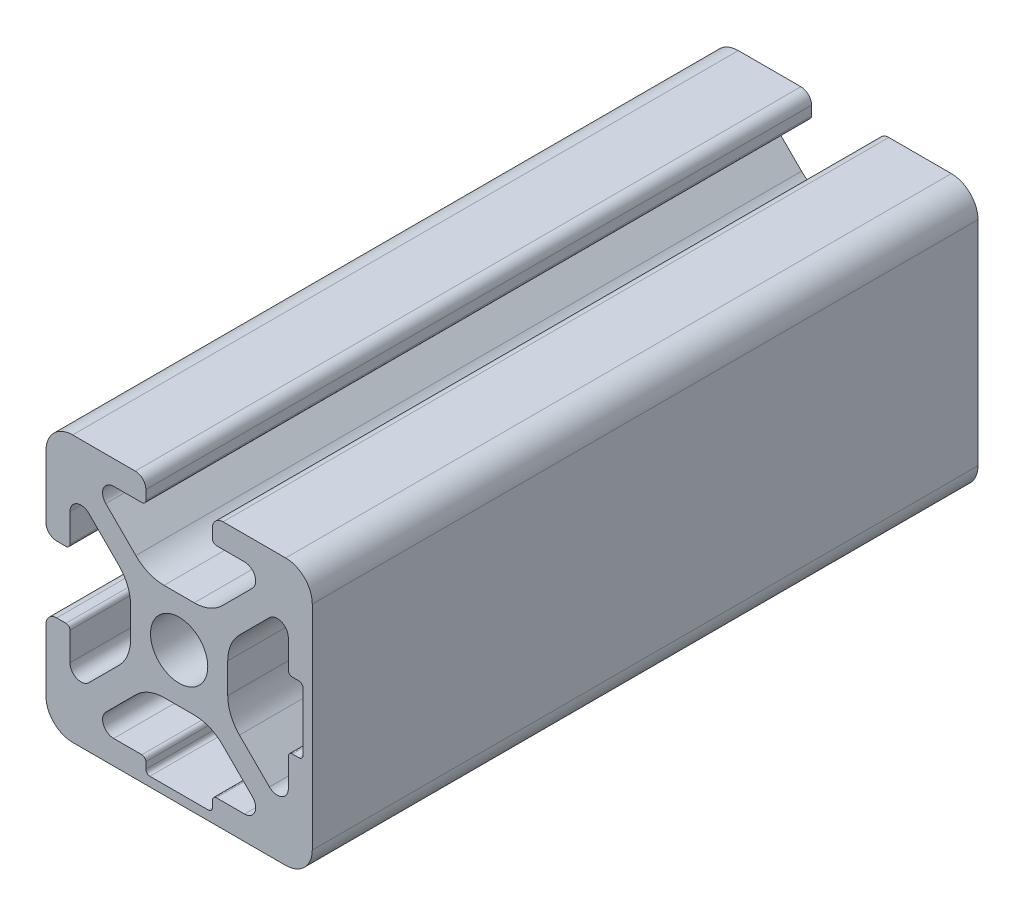
SolidWorks part; units mm, degrees
ref_plane "Plan de face" through (0, 0, 0) normal (0, 0, 1) x (1, 0, 0)
ref_plane "Plan de dessus" through (0, 0, 0) normal (0, 1, 0) x (1, 0, 0)
ref_plane "Plan de droite" through (0, 0, 0) normal (1, 0, 0) x (0, 0, -1)
ref_plane "Plan1" through (0, 0, 0) normal (0, 0, -1) x (-1, 0, 0)
sketch "Esquisse1" plane through (0, 0, 0) normal (0, 0, -1) x (-1, 0, 0)
  line L0 (-18, 0) -> (-2, 0)
  line L1 (0, 2) -> (0, 6.7)
  line L2 (-0.8, 7.5) -> (-1.5, 7.5)
  line L3 (-1.8, 7.2) -> (-1.8, 5.0816)
  line L4 (-3.2196, 4.4936) -> (-5.4713, 6.7453)
  line L5 (-6.35, 8.8666) -> (-6.35, 11.1334)
  line L6 (-5.4713, 13.2547) -> (-3.2196, 15.5064)
  line L7 (-1.8, 14.9184) -> (-1.8, 12.8)
  line L8 (-1.5, 12.5) -> (-0.8, 12.5)
  line L9 (0, 13.3) -> (0, 18)
  line L10 (-2, 20) -> (-6.7, 20)
  line L11 (-7.5, 19.2) -> (-7.5, 18.5)
  line L12 (-7.2, 18.2) -> (-5.0816, 18.2)
  line L13 (-4.4936, 16.7804) -> (-6.7453, 14.5287)
  line L14 (-8.8666, 13.65) -> (-11.1334, 13.65)
  line L15 (-13.2547, 14.5287) -> (-15.5064, 16.7804)
  line L16 (-14.9184, 18.2) -> (-12.8, 18.2)
  line L17 (-12.5, 18.5) -> (-12.5, 19.2)
  line L18 (-13.3, 20) -> (-18, 20)
  line L19 (-20, 18) -> (-20, 2)
  line L20 (-16.779, 15.5062) -> (-14.5287, 13.2559)
  line L21 (-13.65, 11.1346) -> (-13.65, 8.8654)
  line L22 (-14.5287, 6.7441) -> (-16.779, 4.4938)
  line L23 (-18.2, 5.0824) -> (-18.2, 7.2)
  line L24 (-18.5, 7.5) -> (-19, 7.5)
  line L25 (-19.3, 7.8) -> (-19.3, 12.2)
  line L26 (-19, 12.5) -> (-18.5, 12.5)
  line L27 (-18.2, 12.8) -> (-18.2, 14.9176)
  line L28 (-15.5062, 3.221) -> (-13.2559, 5.4713)
  line L29 (-11.1346, 6.35) -> (-8.8654, 6.35)
  line L30 (-6.7441, 5.4713) -> (-4.4938, 3.221)
  line L31 (-5.0824, 1.8) -> (-7.2, 1.8)
  line L32 (-7.5, 1.5) -> (-7.5, 1)
  line L33 (-7.8, 0.7) -> (-12.2, 0.7)
  line L34 (-12.5, 1) -> (-12.5, 1.5)
  line L35 (-12.8, 1.8) -> (-14.9176, 1.8)
  arc A0 (-20, 2) -> (-18, 0) centre (-18, 2) ccw
  arc A1 (-2, 0) -> (0, 2) centre (-2, 2) ccw
  arc A2 (0, 6.7) -> (-0.8, 7.5) centre (-0.8, 6.7) ccw
  arc A3 (-1.5, 7.5) -> (-1.8, 7.2) centre (-1.5, 7.2) ccw
  arc A4 (-1.8, 5.0816) -> (-3.2196, 4.4936) centre (-2.6316, 5.0816) cw
  arc A5 (-5.4713, 6.7453) -> (-6.35, 8.8666) centre (-3.35, 8.8666) cw
  arc A6 (-6.35, 11.1334) -> (-5.4713, 13.2547) centre (-3.35, 11.1334) cw
  arc A7 (-3.2196, 15.5064) -> (-1.8, 14.9184) centre (-2.6316, 14.9184) cw
  arc A8 (-1.8, 12.8) -> (-1.5, 12.5) centre (-1.5, 12.8) ccw
  arc A9 (-0.8, 12.5) -> (0, 13.3) centre (-0.8, 13.3) ccw
  arc A10 (0, 18) -> (-2, 20) centre (-2, 18) ccw
  arc A11 (-6.7, 20) -> (-7.5, 19.2) centre (-6.7, 19.2) ccw
  arc A12 (-7.5, 18.5) -> (-7.2, 18.2) centre (-7.2, 18.5) ccw
  arc A13 (-5.0816, 18.2) -> (-4.4936, 16.7804) centre (-5.0816, 17.3684) cw
  arc A14 (-6.7453, 14.5287) -> (-8.8666, 13.65) centre (-8.8666, 16.65) cw
  arc A15 (-11.1334, 13.65) -> (-13.2547, 14.5287) centre (-11.1334, 16.65) cw
  arc A16 (-15.5064, 16.7804) -> (-14.9184, 18.2) centre (-14.9184, 17.3684) cw
  arc A17 (-12.8, 18.2) -> (-12.5, 18.5) centre (-12.8, 18.5) ccw
  arc A18 (-12.5, 19.2) -> (-13.3, 20) centre (-13.3, 19.2) ccw
  arc A19 (-18, 20) -> (-20, 18) centre (-18, 18) ccw
  circle A20 centre (-10, 10) radius 2.15
  arc A21 (-18.2, 14.9176) -> (-16.779, 15.5062) centre (-17.3676, 14.9176) cw
  arc A22 (-14.5287, 13.2559) -> (-13.65, 11.1346) centre (-16.65, 11.1346) cw
  arc A23 (-13.65, 8.8654) -> (-14.5287, 6.7441) centre (-16.65, 8.8654) cw
  arc A24 (-16.779, 4.4938) -> (-18.2, 5.0824) centre (-17.3676, 5.0824) cw
  arc A25 (-18.2, 7.2) -> (-18.5, 7.5) centre (-18.5, 7.2) ccw
  arc A26 (-19, 7.5) -> (-19.3, 7.8) centre (-19, 7.8) cw
  arc A27 (-19.3, 12.2) -> (-19, 12.5) centre (-19, 12.2) cw
  arc A28 (-18.5, 12.5) -> (-18.2, 12.8) centre (-18.5, 12.8) ccw
  arc A29 (-14.9176, 1.8) -> (-15.5062, 3.221) centre (-14.9176, 2.6324) cw
  arc A30 (-13.2559, 5.4713) -> (-11.1346, 6.35) centre (-11.1346, 3.35) cw
  arc A31 (-8.8654, 6.35) -> (-6.7441, 5.4713) centre (-8.8654, 3.35) cw
  arc A32 (-4.4938, 3.221) -> (-5.0824, 1.8) centre (-5.0824, 2.6324) cw
  arc A33 (-7.2, 1.8) -> (-7.5, 1.5) centre (-7.2, 1.5) ccw
  arc A34 (-7.5, 1) -> (-7.8, 0.7) centre (-7.8, 1) cw
  arc A35 (-12.2, 0.7) -> (-12.5, 1) centre (-12.2, 1) cw
  arc A36 (-12.5, 1.5) -> (-12.8, 1.8) centre (-12.8, 1.5) ccw
extrude "Boss.-Extru.1" add sketch "Esquisse1" against normal blind 50
